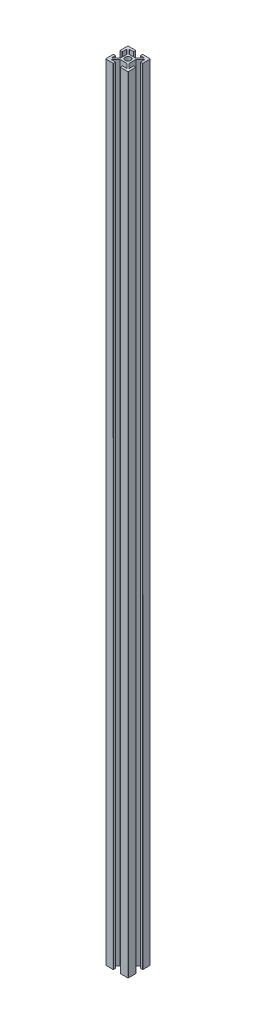
SolidWorks part; units mm, degrees
ref_plane "Front Plane" through (0, 0, 0) normal (0, 0, 1) x (1, 0, 0)
ref_plane "Top Plane" through (0, 0, 0) normal (0, 1, 0) x (1, 0, 0)
ref_plane "Right Plane" through (0, 0, 0) normal (1, 0, 0) x (0, 0, -1)
sketch "Sketch1" plane through (0, 0, 0) normal (0, 1, 0) x (1, 0, 0)
  line L0 (-9.8963, 3) -> (-8.1963, 3)
  line L3 (-3.1963, 10) -> (-9.6963, 10)
  line L4 (-10.0463, 3.15) -> (-10.0463, 9.65)
  line L7 (2.9332, 4) -> (-2.9332, 4)
  line L8 (-4, -2.9454) -> (-4, 2.9454)
  line L9 (-8.0463, 3.15) -> (-8.0463, 6.5862)
  line L10 (-6.6144, 8) -> (-3.1963, 8)
  line L11 (-3.0463, 8.15) -> (-3.0463, 9.85)
  line L12 (-8.0463, 8) -> (-4, 4) construction
  line L13 (-7.7908, 6.6929) -> (-4, 2.9454)
  line L14 (-6.7198, 7.7433) -> (-2.9332, 4)
  line L15 (8.0463, 8) -> (4, 4) construction
  line L22 (0, 0) -> (0, 11.6886) construction
  line L25 (0, 0) -> (-14.9841, 0) construction
  line L27 (6.7198, 7.7433) -> (2.9332, 4)
  line L28 (7.7908, 6.6929) -> (4, 2.9454)
  line L46 (3.0463, 8.15) -> (3.0463, 9.85)
  line L47 (6.6144, 8) -> (3.1963, 8)
  line L48 (8.0463, 3.15) -> (8.0463, 6.5862)
  line L49 (4, -2.9454) -> (4, 2.9454)
  line L50 (10.0463, 3.15) -> (10.0463, 9.65)
  line L51 (3.1963, 10) -> (9.6963, 10)
  line L52 (9.8963, 3) -> (8.1963, 3)
  line L53 (8.0463, -8) -> (4, -4) construction
  line L54 (-8.0463, -8) -> (-4, -4) construction
  line L55 (9.8963, -3) -> (8.1963, -3)
  line L56 (3.1963, -10) -> (9.6963, -10)
  line L57 (10.0463, -3.15) -> (10.0463, -9.65)
  line L58 (8.0463, -3.15) -> (8.0463, -6.5862)
  line L59 (6.6144, -8) -> (3.1963, -8)
  line L60 (3.0463, -8.15) -> (3.0463, -9.85)
  line L61 (7.7908, -6.6929) -> (4, -2.9454)
  line L62 (6.7198, -7.7433) -> (2.9332, -4)
  line L63 (-6.7198, -7.7433) -> (-2.9332, -4)
  line L64 (-7.7908, -6.6929) -> (-4, -2.9454)
  line L65 (-3.0463, -8.15) -> (-3.0463, -9.85)
  line L66 (-6.6144, -8) -> (-3.1963, -8)
  line L67 (-8.0463, -3.15) -> (-8.0463, -6.5862)
  line L68 (2.9332, -4) -> (-2.9332, -4)
  line L69 (-10.0463, -3.15) -> (-10.0463, -9.65)
  line L70 (-3.1963, -10) -> (-9.6963, -10)
  line L71 (-9.8963, -3) -> (-8.1963, -3)
  circle A0 centre (0, 0) radius 2.5
  arc A1 (-10.0463, 9.65) -> (-9.6963, 10) centre (-9.6963, 9.65) cw
  arc A2 (-9.8963, 3) -> (-10.0463, 3.15) centre (-9.8963, 3.15) cw
  arc A3 (-8.1963, 3) -> (-8.0463, 3.15) centre (-8.1963, 3.15) ccw
  arc A4 (-3.1963, 10) -> (-3.0463, 9.85) centre (-3.1963, 9.85) cw
  arc A5 (-3.1963, 8) -> (-3.0463, 8.15) centre (-3.1963, 8.15) ccw
  arc A6 (-6.7198, 7.7433) -> (-6.6144, 8) centre (-6.6144, 7.85) cw
  arc A7 (-7.7908, 6.6929) -> (-8.0463, 6.5862) centre (-7.8963, 6.5862) ccw
  arc A8 (7.7908, 6.6929) -> (8.0463, 6.5862) centre (7.8963, 6.5862) cw
  arc A9 (6.7198, 7.7433) -> (6.6144, 8) centre (6.6144, 7.85) ccw
  arc A10 (3.1963, 8) -> (3.0463, 8.15) centre (3.1963, 8.15) cw
  arc A11 (3.1963, 10) -> (3.0463, 9.85) centre (3.1963, 9.85) ccw
  arc A12 (8.1963, 3) -> (8.0463, 3.15) centre (8.1963, 3.15) cw
  arc A13 (9.8963, 3) -> (10.0463, 3.15) centre (9.8963, 3.15) ccw
  arc A14 (10.0463, 9.65) -> (9.6963, 10) centre (9.6963, 9.65) ccw
  arc A15 (10.0463, -9.65) -> (9.6963, -10) centre (9.6963, -9.65) cw
  arc A16 (9.8963, -3) -> (10.0463, -3.15) centre (9.8963, -3.15) cw
  arc A17 (8.1963, -3) -> (8.0463, -3.15) centre (8.1963, -3.15) ccw
  arc A18 (3.1963, -10) -> (3.0463, -9.85) centre (3.1963, -9.85) cw
  arc A19 (3.1963, -8) -> (3.0463, -8.15) centre (3.1963, -8.15) ccw
  arc A20 (6.7198, -7.7433) -> (6.6144, -8) centre (6.6144, -7.85) cw
  arc A21 (7.7908, -6.6929) -> (8.0463, -6.5862) centre (7.8963, -6.5862) ccw
  arc A22 (-7.7908, -6.6929) -> (-8.0463, -6.5862) centre (-7.8963, -6.5862) cw
  arc A23 (-6.7198, -7.7433) -> (-6.6144, -8) centre (-6.6144, -7.85) ccw
  arc A24 (-3.1963, -8) -> (-3.0463, -8.15) centre (-3.1963, -8.15) cw
  arc A25 (-3.1963, -10) -> (-3.0463, -9.85) centre (-3.1963, -9.85) ccw
  arc A26 (-8.1963, -3) -> (-8.0463, -3.15) centre (-8.1963, -3.15) cw
  arc A27 (-9.8963, -3) -> (-10.0463, -3.15) centre (-9.8963, -3.15) ccw
  arc A28 (-10.0463, -9.65) -> (-9.6963, -10) centre (-9.6963, -9.65) ccw
  point P8 (-10.0463, 10)
  point P27 (-10.0463, 3)
  point P30 (3.0463, 8)
  point P31 (10.0463, -10)
  point P50 (4, 0)
  point P55 (-8.0463, 3)
  point P58 (-3.0463, 10)
  point P61 (-3.0463, 8)
  point P63 (0, 4)
  point P65 (3.0463, 10)
  point P66 (8.0463, 3)
  point P67 (10.0463, 3)
  point P68 (10.0463, 10)
  point P118 (-4, 0)
  point P119 (10.0463, -3)
  point P120 (8.0463, -3)
  point P121 (3.0463, -10)
  point P122 (0, -4)
  point P123 (-3.0463, -8)
  point P124 (-3.0463, -10)
  point P125 (-8.0463, -3)
  point P126 (3.0463, -8)
  point P127 (-10.0463, -3)
  point P128 (-10.0463, -10)
  dimension "D2" = 0.35
  dimension "D3" = 0.15
  dimension "D4" = 0.15
  dimension "D5" = 0.15
  dimension "D12" = 0.15
  dimension "D13" = 0.15
  dimension "D14" = 0.15
  dimension "D6" = 2
  dimension "D7" = 7
  dimension "D8" = 7
  dimension "D9" = 2
  dimension "D10" = 0.75
  dimension "D11" = 0.75
extrude "Boss-Extrude2" add sketch "Sketch1" along normal blind 700
